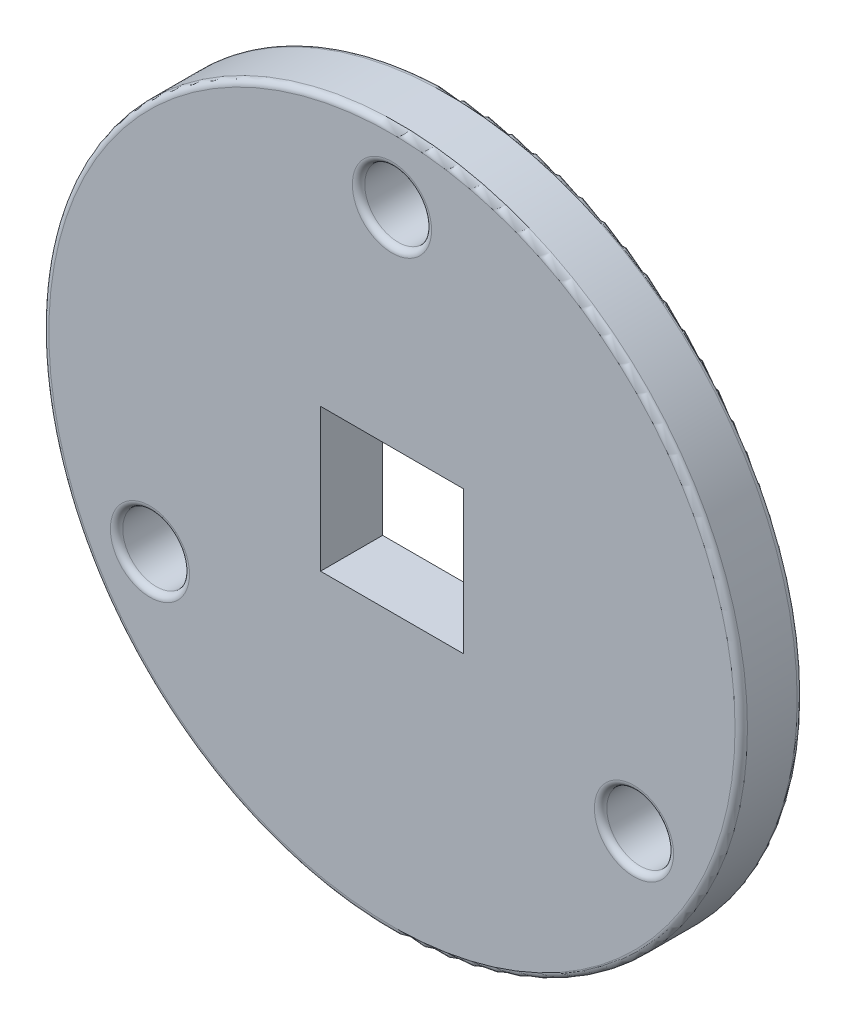
SolidWorks part; units mm, degrees
ref_plane "Front Plane" through (0, 0, 0) normal (0, 0, 1) x (1, 0, 0)
ref_plane "Top Plane" through (0, 0, 0) normal (0, 1, 0) x (1, 0, 0)
ref_plane "Right Plane" through (0, 0, 0) normal (1, 0, 0) x (0, 0, -1)
sketch "Sketch1" plane through (0, 0, 0) normal (0, 0, 1) x (1, 0, 0)
  line L1 (-23, 23) -> (23, 23)
  line L2 (-23, 23) -> (-23, -23)
  line L3 (-23, -23) -> (23, -23)
  line L4 (23, 23) -> (23, -23)
  circle A0 centre (0, 0) radius 112.5
  circle A2 centre (0, 90) radius 10.75
  circle A6 centre (77.9423, -45) radius 10.75
  circle A7 centre (-77.9423, -45) radius 10.75
  point P11 (0, 0)
  point P14 (0, 23)
  point P15 (0, 0)
  point P16 (-23, 0)
  dimension "D2" = 21.5
  dimension "D3" = 225
  dimension "D5" = 46
  dimension "D1" = 90
  dimension "D4" = 3
extrude "Boss-Extrude1" add sketch "Sketch1" along normal blind 20
fillet "Fillet9" radius 2 8 edges at (88.6923, -45, 0) (10.75, 90, 0) (-67.1923, -45, 0) (-67.1923, -45, 20) (10.75, 90, 20) (88.6923, -45, 20) (112.5, 0, 0) (112.5, 0, 20)
